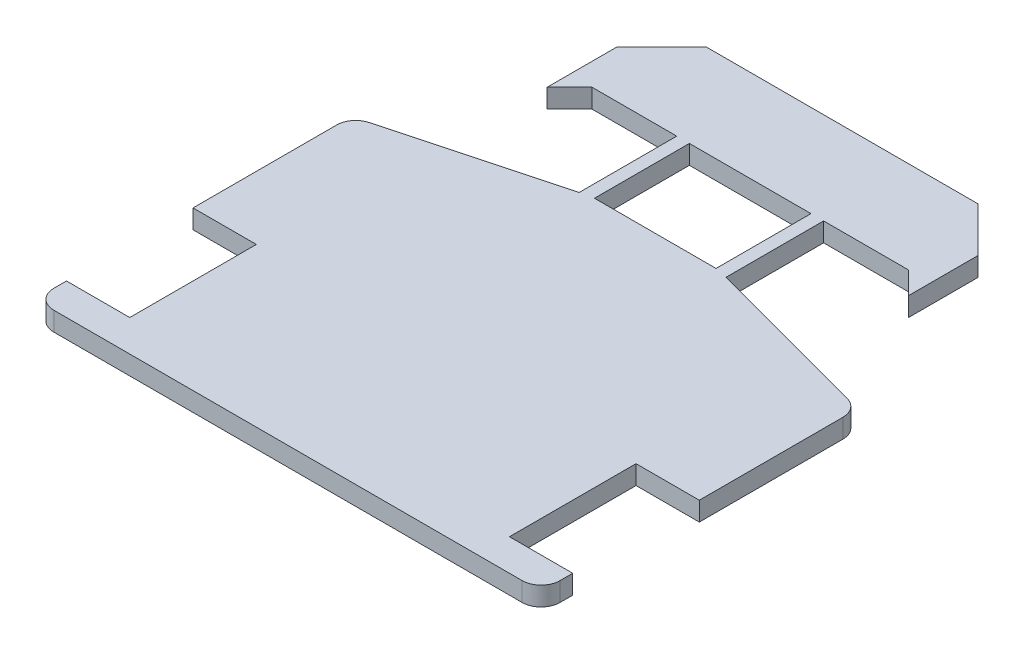
SolidWorks part; units mm, degrees
ref_plane "Front Plane" through (0, 0, 0) normal (0, 0, 1) x (1, 0, 0)
ref_plane "Top Plane" through (0, 0, 0) normal (0, 1, 0) x (1, 0, 0)
ref_plane "Right Plane" through (0, 0, 0) normal (1, 0, 0) x (0, 0, -1)
sketch "Sketch1" plane through (0, 0, 0) normal (0, 1, 0) x (1, 0, 0)
  line L0 (0, 0) -> (-37, 0)
  line L1 (0, 0) -> (37, 0)
  line L2 (40, 3) -> (40, 5)
  line L3 (40, 5) -> (30, 5)
  line L4 (30, 5) -> (30, 25)
  line L5 (30, 25) -> (40, 25)
  line L6 (40, 25) -> (40, 47.698)
  line L8 (-40, 3) -> (-40, 5)
  line L9 (-40, 5) -> (-30, 5)
  line L10 (-30, 5) -> (-30, 25)
  line L11 (-30, 25) -> (-40, 25)
  line L12 (-40, 25) -> (-40, 47.698)
  line L14 (-40, 50) -> (40, 50) construction
  line L30 (0, 0) -> (0, 116.63) construction
  line L31 (-37.7765, 50.5958) -> (-10.3815, 57.9363)
  line L33 (37.7765, 50.5958) -> (10.3815, 57.9363)
  line L40 (-9.605, 58.0385) -> (9.605, 58.0385)
  arc A0 (-40, 47.698) -> (-37.7765, 50.5958) centre (-37, 47.698) cw
  arc A1 (40, 47.698) -> (37.7765, 50.5958) centre (37, 47.698) ccw
  arc A2 (9.605, 58.0385) -> (10.3815, 57.9363) centre (9.605, 55.0385) cw
  arc A3 (-9.605, 58.0385) -> (-10.3815, 57.9363) centre (-9.605, 55.0385) ccw
  arc A4 (-37, 0) -> (-40, 3) centre (-37, 3) cw
  arc A5 (37, 0) -> (40, 3) centre (37, 3) ccw
  point P25 (10, 58.0385)
  point P28 (-10, 58.0385)
  point P31 (-40, 0)
  point P34 (40, 0)
  dimension "D14" = 3
  dimension "D15" = 3
  dimension "D16" = 3
  dimension "D17" = 3
  dimension "D1" = 10
  dimension "D2" = 20
  dimension "D3" = 25
  dimension "D4" = 40
  dimension "D5" = 25
  dimension "D6" = 10
  dimension "D7" = 20
  dimension "D8" = 15
  dimension "D9" = 15
  dimension "D10" = 5
  dimension "D11" = 40
  dimension "D12" = 40
  dimension "D13" = 20
extrude "Boss-Extrude1" add sketch "Sketch1" along normal blind 3
sketch "Sketch3" plane through (0, 3, 0) normal (0, 1, 0) x (1, 0, 0)
  line L0 (-9.605, 58.0385) -> (-9.605, 73.0385)
  line L3 (9.605, 58.0385) -> (9.605, 73.0385)
  line L8 (-9.605, 73.0385) -> (-11.605, 73.0385)
  line L16 (-11.605, 73.0385) -> (-11.605, 57.6084)
  line L17 (-37.7765, 50.5958) -> (-10.3815, 57.9363) construction
  line L18 (-11.605, 57.6084) -> (-9.605, 58.0385)
  line L19 (9.605, 73.0385) -> (11.605, 73.0385)
  line L20 (11.605, 73.0385) -> (11.605, 57.6084)
  line L21 (37.7765, 50.5958) -> (10.3815, 57.9363) construction
  line L22 (11.605, 57.6084) -> (9.605, 58.0385)
  dimension "D1" = 2
extrude "Boss-Extrude2" add sketch "Sketch3" against normal blind 3
sketch "Sketch4" plane through (0, 3, 0) normal (0, 1, 0) x (1, 0, 0)
  line L0 (0, 73.0385) -> (0, 58.0385) construction
  line L2 (-9.605, 58.0385) -> (9.605, 58.0385) construction
  line L3 (0, 73.0385) -> (-25, 73.0385)
  line L4 (0, 73.0385) -> (25, 73.0385)
  line L5 (25, 73.0385) -> (28.5355, 69.5029)
  line L8 (0, 73.0385) -> (0, 82.9485) construction
  line L19 (-25, 73.0385) -> (-28.5355, 69.5029)
  line L23 (-28.5355, 69.5029) -> (-28.5355, 80.5029)
  line L24 (-28.5355, 80.5029) -> (-21.4645, 87.574)
  line L25 (28.5355, 69.5029) -> (28.5355, 80.5029)
  line L26 (28.5355, 80.5029) -> (21.4645, 87.574)
  line L27 (-21.4645, 87.574) -> (21.4645, 87.574)
  dimension "D5" = 15
  dimension "D6" = 5
  dimension "D1" = 25
  dimension "D2" = 10
  dimension "D3" = 135
  dimension "D4" = 11
extrude "Boss-Extrude3" add sketch "Sketch4" against normal blind 3
